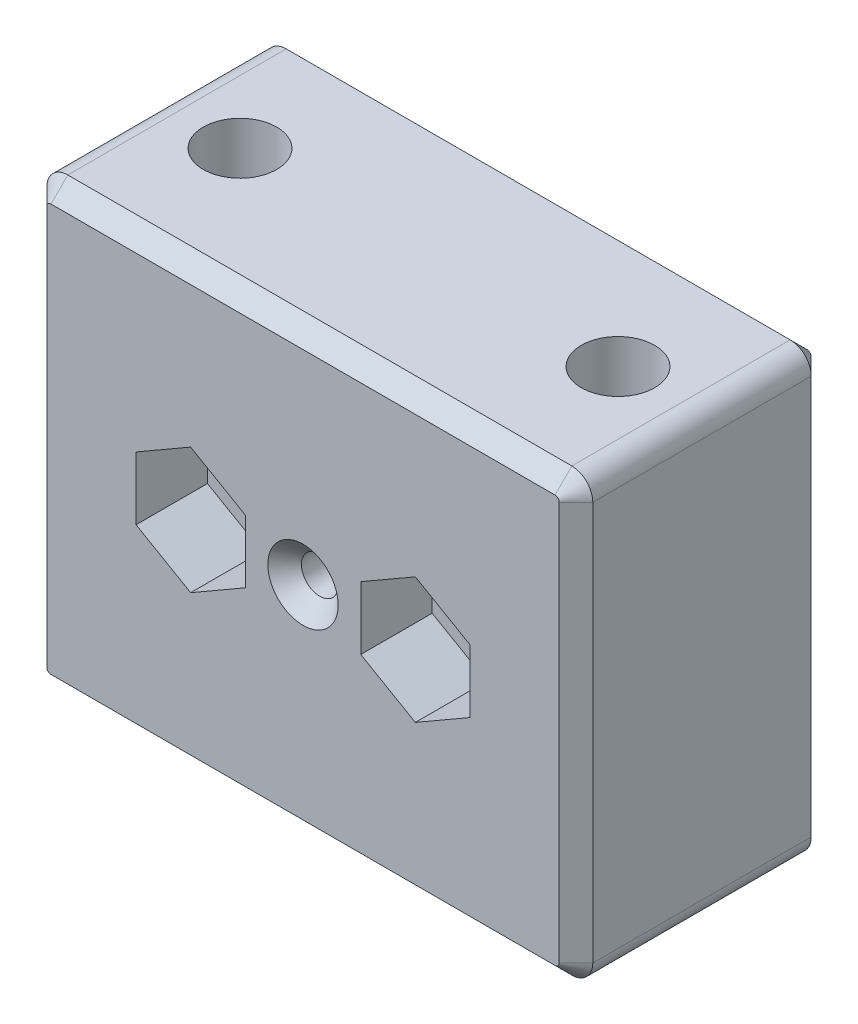
SolidWorks part; units mm, degrees
ref_plane "Alzado" through (0, 0, 0) normal (0, 0, 1) x (1, 0, 0)
ref_plane "Planta" through (0, 0, 0) normal (0, 1, 0) x (1, 0, 0)
ref_plane "Vista lateral" through (0, 0, 0) normal (1, 0, 0) x (0, 0, -1)
sketch "Croquis1" plane through (0, 0, 0) normal (0, 0, 1) x (1, 0, 0)
  line L1 (-13, 10.5) -> (13, 10.5)
  line L2 (-13, 10.5) -> (-13, -10.5)
  line L3 (-13, -10.5) -> (13, -10.5)
  line L4 (13, 10.5) -> (13, -10.5)
  line L5 (-13, 10.5) -> (13, -10.5) construction
  line L6 (-13, -10.5) -> (13, 10.5) construction
  point P0 (0, 0)
  dimension "D1" = 21
  dimension "D2" = 26
extrude "Saliente-Extruir1" add sketch "Croquis1" along normal mid plane 12
sketch "Croquis2" plane through (0, -10.5, 0) normal (0, -1, 0) x (1, 0, 0)
  line L0 (9, 0) -> (-9, 0) construction
  circle A0 centre (-9, 0) radius 1.75
  circle A1 centre (9, 0) radius 1.75
  point P4 (0, 0)
  dimension "D2" = 3.5
  dimension "D1" = 18
extrude "Cortar-Extruir1" cut sketch "Croquis2" against normal through all both and the other way through all
sketch "Croquis3" plane through (0, 0, 6) normal (0, 0, 1) x (1, 0, 0)
  circle A0 centre (0, 0) radius 0.875
  dimension "D1" = 1.75
extrude "Cortar-Extruir2" cut sketch "Croquis3" against normal blind 15
fillet "Redondeo1" radius 1 4 edges at (13, 10.5, 0) (-13, 10.5, 0) (13, -10.5, 0) (-13, -10.5, 0)
chamfer "Chaflán1" distance 0.8 angle 45 16 edges at (0, 10.5, -6) (-13, 0, -6) (0, -10.5, -6) (13, 0, -6) (0, -10.5, 6) (-13, 0, 6) (0, 10.5, 6) (13, 0, 6) (-12.7071, 10.2071, -6) (-12.7071, -10.2071, -6) (12.7071, -10.2071, -6) (12.7071, 10.2071, -6) (12.7071, -10.2071, 6) (-12.7071, -10.2071, 6) (-12.7071, 10.2071, 6) (12.7071, 10.2071, 6)
chamfer "Chaflán2" distance 0.8 angle 45 2 edges at (0.875, 0, -6) (0.875, 0, 6)
sketch "Croquis4" plane through (0, 0, 6) normal (0, 0, 1) x (1, 0, 0)
  line L0 (-5.35, 0) -> (5.35, 0) construction
  line L2 (-5.35, 3.0022) -> (-7.95, 1.5011)
  line L3 (-7.95, 1.5011) -> (-7.95, -1.5011)
  line L4 (-7.95, -1.5011) -> (-5.35, -3.0022)
  line L5 (-5.35, -3.0022) -> (-2.75, -1.5011)
  line L6 (-2.75, -1.5011) -> (-2.75, 1.5011)
  line L7 (-2.75, 1.5011) -> (-5.35, 3.0022)
  line L8 (5.35, 3.0022) -> (2.75, 1.5011)
  line L9 (2.75, 1.5011) -> (2.75, -1.5011)
  line L10 (2.75, -1.5011) -> (5.35, -3.0022)
  line L11 (5.35, -3.0022) -> (7.95, -1.5011)
  line L12 (7.95, -1.5011) -> (7.95, 1.5011)
  line L13 (7.95, 1.5011) -> (5.35, 3.0022)
  circle A0 centre (-5.35, 0) radius 1.7 construction
  circle A1 centre (5.35, 0) radius 1.7 construction
  circle A2 centre (-5.35, 0) radius 2.6 construction
  circle A3 centre (5.35, 0) radius 2.6 construction
  point P9 (0, 0)
  dimension "D1" = 3.4
  dimension "D2" = 5.2
  dimension "D3" = 5.5
extrude "Cortar-Extruir3" cut sketch "Croquis4" against normal blind 3.4
sketch "Croquis5" plane through (0, 0, 2.6) normal (0, 0, 1) x (1, 0, 0)
  circle A0 centre (5.35, 0) radius 1.7 construction
  circle A1 centre (-5.35, 0) radius 1.7 construction
  circle A2 centre (5.35, 0) radius 1.7
  circle A3 centre (-5.35, 0) radius 1.7
extrude "Cortar-Extruir4" cut sketch "Croquis5" against normal blind 40
